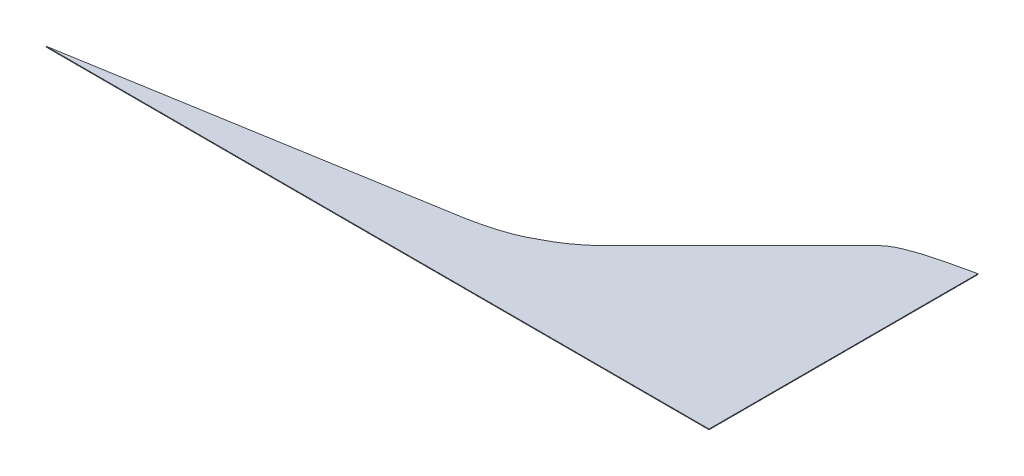
SolidWorks part; units mm, degrees
ref_plane "Front Plane" through (0, 0, 0) normal (0, 0, 1) x (1, 0, 0)
ref_plane "Top Plane" through (0, 0, 0) normal (0, 1, 0) x (1, 0, 0)
ref_plane "Right Plane" through (0, 0, 0) normal (1, 0, 0) x (0, 0, -1)
sketch "Sketch2" plane through (0, 0, 0) normal (0, 1, 0) x (1, 0, 0)
  line L0 (-114.4502, 13.7247) -> (4685.5498, 13.7247) construction
  line L1 (629.731, 277.2153) -> (2214.3793, 544.3024)
  line L2 (2615.9095, 739.5613) -> (3219.092, 1342.7438)
  line L3 (629.731, 277.2153) -> (3554.0454, 277.2153)
  line L4 (3554.0454, 277.2153) -> (3554.0454, 1463.3263)
  spline S0 degree 3 poles (2214.3793, 544.3024) (2299.4931, 561.9204) (2384.4408, 583.3548) (2459.6066, 628.9741) knots 0 0 0 0 1 1 1 1
  spline S1 degree 2 poles (2459.6066, 628.9741) (2544.9098, 672.4296) (2615.9095, 739.5613) knots 0 0 0 1 1 1
  spline S2 degree 2 poles (3219.092, 1342.7438) (3249.7929, 1375.6673) (3294.1236, 1392.5056) knots 0 0 0 1 1 1
  spline S3 degree 1 poles (3294.1236, 1392.5056) (3355.5849, 1415.1711) knots 0 0 1 1
  spline S4 degree 1 poles (3355.5849, 1415.1711) (3426.8592, 1434.3278) knots 0 0 1 1
  spline S5 degree 1 poles (3426.8592, 1434.3278) (3554.0454, 1463.3263) knots 0 0 1 1
extrude "Boss-Extrude2" add sketch "Sketch2" against normal blind 3.1229
scale "Scale6" scale about centroid uniform scaling yes scale factor 8.133897
